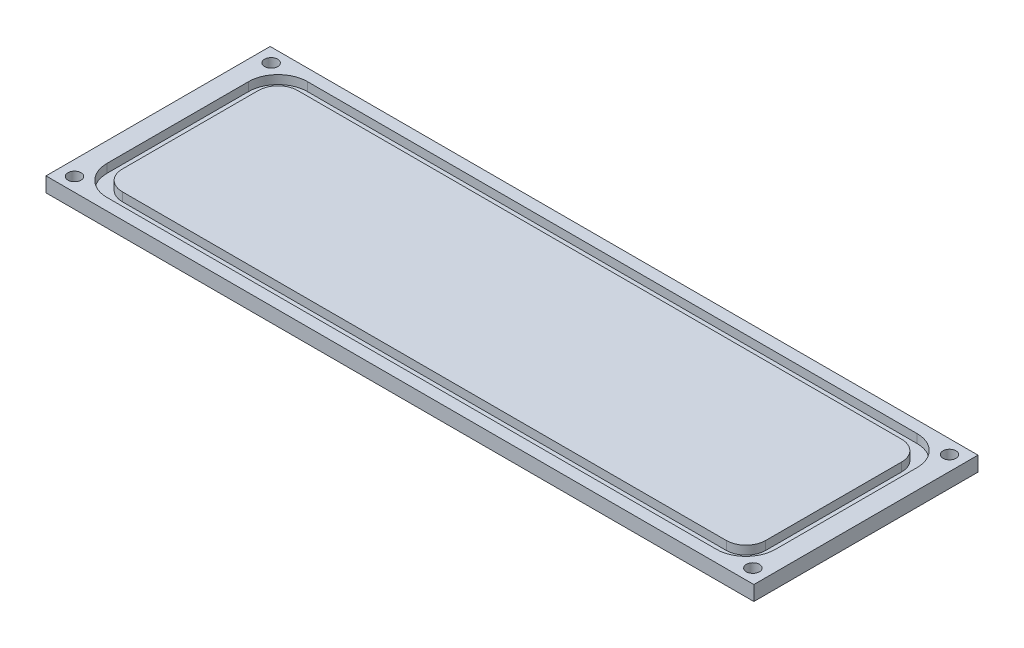
SolidWorks part; units mm, degrees
material "6061-T6 (SS)"
ref_plane "Front" through (0, 0, 0) normal (0, 0, 1) x (1, 0, 0)
ref_plane "Top" through (0, 0, 0) normal (0, 1, 0) x (1, 0, 0)
ref_plane "Right" through (0, 0, 0) normal (1, 0, 0) x (0, 0, -1)
sketch "Sketch1" plane through (0, 0, 0) normal (0, 1, 0) x (1, 0, 0)
  line L1 (0, 0) -> (228.6, 0)
  line L2 (0, 0) -> (0, 72.39)
  line L3 (0, 72.39) -> (228.6, 72.39)
  line L4 (228.6, 0) -> (228.6, 72.39)
  dimension "D1" = 228.6
  dimension "D2" = 72.39
extrude "Boss-Extrude1" add sketch "Sketch1" along normal blind 4.7625
sketch "Sketch2" plane through (0, 4.7625, 0) normal (0, 1, 0) x (1, 0, 0)
  line L0 (0, 72.39) -> (0, 0) construction
  line L1 (6.35, 3.81) -> (222.25, 3.81)
  line L2 (6.35, 3.81) -> (6.35, 68.58)
  line L3 (6.35, 68.58) -> (222.25, 68.58)
  line L4 (222.25, 3.81) -> (222.25, 68.58)
  line L5 (10.414, 7.874) -> (218.186, 7.874)
  line L6 (10.414, 7.874) -> (10.414, 64.516)
  line L7 (10.414, 64.516) -> (218.186, 64.516)
  line L8 (218.186, 7.874) -> (218.186, 64.516)
  line L9 (0, 0) -> (228.6, 0) construction
  dimension "D1" = 215.9
  dimension "D2" = 64.77
  dimension "D3" = 4.064
  dimension "D4" = 4.064
  dimension "D5" = 4.064
  dimension "D6" = 4.064
  dimension "D7" = 6.35
  dimension "D8" = 3.81
extrude "Cut-Extrude1" cut sketch "Sketch2" against normal blind 2.794
fillet "Fillet1" radius 9.525 4 edges at (6.35, 3.3655, -3.81) (222.25, 3.3655, -3.81) (222.25, 3.3655, -68.58) (6.35, 3.3655, -68.58)
fillet "Fillet2" radius 6.35 4 edges at (10.414, 3.3655, -7.874) (218.186, 3.3655, -7.874) (218.186, 3.3655, -64.516) (10.414, 3.3655, -64.516)
hole_wizard "#19 (0.166) Diameter Hole1" positions "Sketch3" profile "Sketch4" hole size "#19" standard "ANSI Inch" end condition through all
sketch "Sketch3" plane through (0, 4.7625, 0) normal (0, 1, 0) x (1, 0, 0)
  line L0 (0, 72.39) -> (0, 0) construction
  line L1 (0, 0) -> (228.6, 0) construction
  point P0 (4.7625, 4.445)
  dimension "D1" = 4.7625
  dimension "D2" = 4.445
sketch "Sketch4" plane through (4.7625, 4.7625, -4.445) normal (1, 0, 0) x (0, 0, 1)
  line L0 (0, 0) -> (0, 4.7625)
  line L1 (0, 4.7625) -> (2.1082, 4.7625)
  line L2 (2.1082, 4.7625) -> (2.1082, 0)
  line L5 (2.1082, 0) -> (0, 0)
  line L11 (0, -6.35) -> (0, 107.95) construction
  dimension "Thru Hole Dia." = 4.2164
  dimension "Thru Hole Depth" = 4.7625
pattern_linear "LPattern1" count 2 spacing 219.075 along (1, 0, 0) count 2 spacing 63.5 along (0, 0, -1) of "#19 (0.166) Diameter Hole1"
